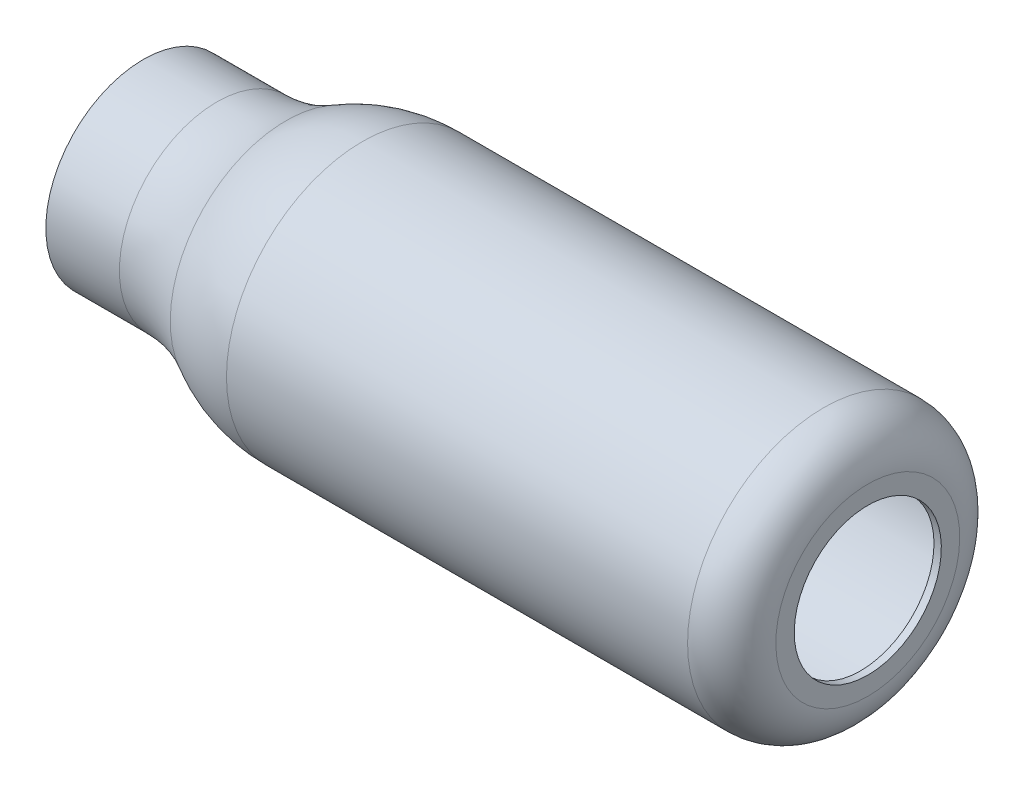
SolidWorks part; units mm, degrees
material "AISI 1020"
ref_plane "Front Plane" through (0, 0, 0) normal (0, 0, 1) x (1, 0, 0)
ref_plane "Top Plane" through (0, 0, 0) normal (0, 1, 0) x (1, 0, 0)
ref_plane "Right Plane" through (0, 0, 0) normal (1, 0, 0) x (0, 0, -1)
sketch "Exhaust Cover Sketch" plane through (0, 0, 0) normal (0, 0, 1) x (1, 0, 0)
  line L0 (0, 0) -> (123.825, 0) construction
  line L4 (0, 15.5575) -> (12.7, 15.5575)
  line L7 (37.8587, 22.225) -> (117.475, 22.225)
  line L8 (0, 16.8275) -> (12.7, 16.8275)
  line L9 (37.8587, 23.495) -> (117.475, 23.495)
  line L10 (125.095, 15.875) -> (125.095, 12.7)
  line L12 (123.825, 15.875) -> (123.825, 12.7)
  line L13 (0, 16.8275) -> (0, 15.5575)
  line L14 (123.825, 12.7) -> (125.095, 12.7)
  arc A0 (12.7, 15.5575) -> (25.2794, 18.8912) centre (12.7, 40.9575) ccw
  arc A3 (12.7, 16.8275) -> (24.6504, 19.9946) centre (12.7, 40.9575) ccw
  arc A4 (24.6504, 19.9946) -> (37.8587, 23.495) centre (37.8587, -3.175) cw
  arc A5 (117.475, 23.495) -> (125.095, 15.875) centre (117.475, 15.875) cw
  arc A7 (25.2794, 18.8912) -> (37.8587, 22.225) centre (37.8587, -3.175) cw
  arc A8 (117.475, 22.225) -> (123.825, 15.875) centre (117.475, 15.875) cw
  dimension "D7" = 25.4
  dimension "D8" = 12.7
  dimension "D1" = 25.4
  dimension "D4" = 123.825
  dimension "D3" = 6.35
  dimension "D2" = 12.7
  dimension "D5" = 15.5575
  dimension "D6" = 22.225
  dimension "D9" = 1.27
revolve "Exhaust Cover" add sketch "Exhaust Cover Sketch" angle 360 about L0
